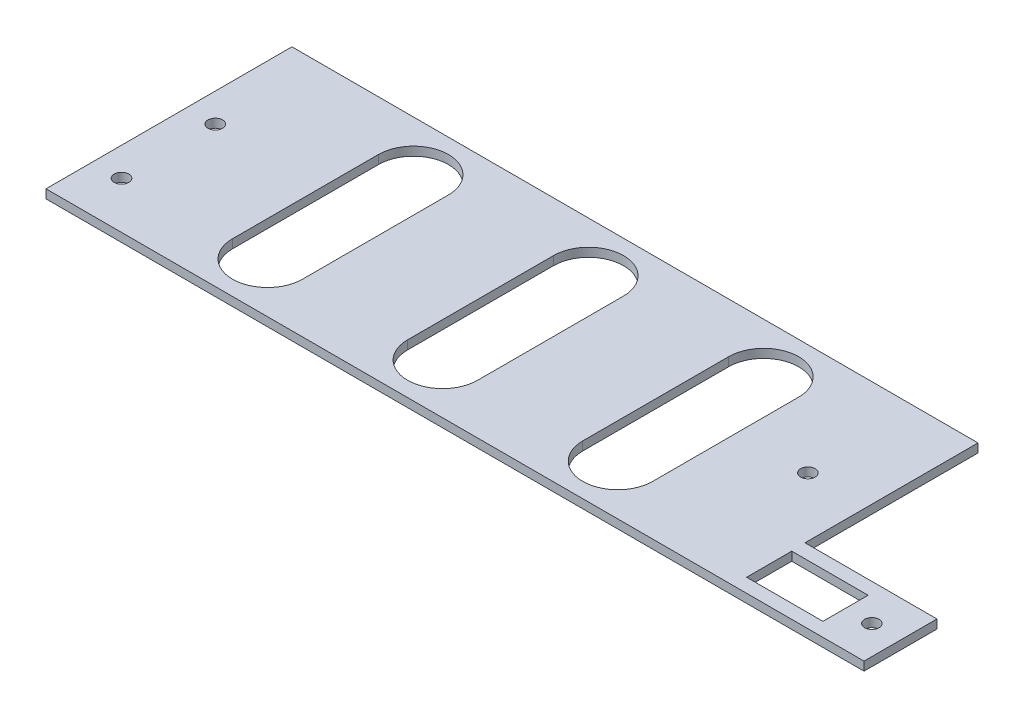
SolidWorks part; units mm, degrees
material "Custom Plastic"
ref_plane "Plan de face" through (0, 0, 0) normal (0, 0, 1) x (1, 0, 0)
ref_plane "Plan de dessus" through (0, 0, 0) normal (0, 1, 0) x (1, 0, 0)
ref_plane "Plan de droite" through (0, 0, 0) normal (1, 0, 0) x (0, 0, -1)
sketch "Esquisse1" plane through (0, 0, 0) normal (0, 1, 0) x (1, 0, 0)
  line L1 (-170.0285, 28.77) -> (110.2715, 28.77) construction
  line L2 (-170.0285, 28.77) -> (-170.0285, -35.5) construction
  line L3 (-170.0285, -35.5) -> (110.2715, -35.5) construction
  line L4 (110.2715, 28.77) -> (110.2715, -35.5) construction
  line L5 (-170.0285, 28.77) -> (110.2715, -35.5) construction
  line L6 (-170.0285, -35.5) -> (110.2715, 28.77) construction
  line L7 (110.2715, 18.77) -> (110.2715, -23) construction
  line L9 (-170.0285, 18.77) -> (-170.0285, -23)
  line L10 (-170.0285, 18.77) -> (-160.0285, 18.77) construction
  line L12 (-170.0285, -35.5) -> (110.2715, -35.5)
  line L13 (110.4715, -10.5) -> (110.4715, -35.5) construction
  line L14 (-160.0285, 28.77) -> (-160.0285, 18.77) construction
  line L15 (65.0578, -2.5147) -> (65.0578, -50002.5147) construction
  line L16 (-170.0285, -23) -> (-160.0285, -23) construction
  line L17 (58.3078, 10.7475) -> (58.3078, -4.4385) construction
  line L18 (-170.2285, -35.5) -> (119.7715, -35.5) construction
  line L19 (-170.0285, 18.77) -> (110.2715, 18.77) construction
  line L21 (110.2715, -23) -> (-170.0285, -23) construction
  line L26 (100.4715, -46.7393) -> (100.4715, -50046.7393) construction
  line L28 (65.0578, 28.77) -> (65.0578, -10.5)
  line L30 (-170.0285, -23) -> (-170.0285, -35.5)
  line L33 (-170.0285, 28.77) -> (-170.0285, 18.77)
  line L34 (-170.0285, 28.77) -> (65.0578, 28.77)
  line L36 (65.0578, -10.5) -> (110.2715, -10.5)
  line L37 (110.2715, -10.5) -> (110.2715, -35.5)
  line L39 (-170.2285, -35.5) -> (-170.2285, -38.5) construction
  line L40 (-170.0285, -35.5) -> (-170.2285, -35.5) construction
  line L41 (110.2715, -35.5) -> (110.4715, -35.5) construction
  line L47 (65.0578, -10.5) -> (119.7715, -10.5) construction
  line L52 (65.0578, 28.77) -> (68.0578, 28.77) construction
  circle A12 centre (100.4715, -23) radius 2.5
  circle A17 centre (-160.2285, -19.4325) radius 2.5
  circle A18 centre (-160.2285, 12.7025) radius 2.5
  circle A20 centre (-160.2285, 12.7025) radius 2.5 construction
  circle A22 centre (-160.2285, -19.4325) radius 2.5 construction
  circle A23 centre (100.4715, -23) radius 2.5 construction
  circle A24 centre (44.8078, 10.7475) radius 2.5
  point P4 (-29.8785, -3.365)
  dimension "D3" = 10
  dimension "D4" = 5
  dimension "D5" = 13.5
  dimension "D7" = 5
  dimension "D1" = 3
  dimension "D2" = 0.2
  dimension "D8" = 0.2
extrude "Boss.-Extru.1" add sketch "Esquisse1" along normal blind 3
sketch "Esquisse2" plane through (0, 3, 0) normal (0, 1, 0) x (1, 0, 0)
  line L0 (-170.0285, 28.77) -> (-170.0285, 38.77) construction
  line L1 (-170.0285, 38.77) -> (-52.4853, 38.77) construction
  line L2 (65.0578, 38.77) -> (65.0578, 28.77) construction
  line L3 (65.0578, -3.365) -> (80.0824, -3.365) construction
  line L4 (100.4715, -23) -> (117.6885, -23) construction
  line L5 (-170.0285, 28.77) -> (-170.0285, -35.5) construction
  line L6 (-52.4853, 38.77) -> (65.0578, 38.77) construction
  line L7 (-111.2569, 38.77) -> (-111.2569, 50038.77) construction
  line L8 (-52.4853, 38.77) -> (-52.4853, 50038.77) construction
  line L9 (6.2862, 38.77) -> (6.2862, 50038.77) construction
  line L10 (-113.7569, 11.635) -> (-113.7569, -18.365)
  line L11 (-108.7569, -18.365) -> (-108.7569, 11.635)
  line L12 (-113.7569, 11.635) -> (-108.7569, 11.635) construction
  line L13 (-108.7569, -18.365) -> (-113.7569, -18.365) construction
  line L14 (-113.7569, -3.365) -> (-108.7569, -3.365) construction
  line L15 (-54.9853, 11.635) -> (-54.9853, -18.365)
  line L16 (-49.9853, -18.365) -> (-49.9853, 11.635)
  line L17 (-54.9853, 11.635) -> (-49.9853, 11.635) construction
  line L18 (-49.9853, -18.365) -> (-54.9853, -18.365) construction
  line L19 (-54.9853, -3.365) -> (-49.9853, -3.365) construction
  line L20 (3.7862, 11.635) -> (3.7862, -18.365)
  line L21 (8.7862, -18.365) -> (8.7862, 11.635)
  line L22 (3.7862, 11.635) -> (8.7862, 11.635) construction
  line L23 (8.7862, -18.365) -> (3.7862, -18.365) construction
  line L24 (3.7862, -3.365) -> (8.7862, -3.365) construction
  line L25 (85.2715, -23) -> (85.2715, -50023) construction
  line L26 (110.2715, -35.5) -> (110.2715, -10.5) construction
  line L27 (85.2715, -18) -> (65.2715, -18)
  line L28 (65.2715, -18) -> (65.2715, -28)
  line L29 (65.2715, -28) -> (85.2715, -28)
  line L30 (85.2715, -28) -> (85.2715, -18)
  arc A0 (-108.7569, 11.635) -> (-113.7569, 11.635) centre (-111.2569, 11.635) ccw
  arc A1 (-108.7569, -18.365) -> (-113.7569, -18.365) centre (-111.2569, -18.365) cw
  arc A2 (-49.9853, 11.635) -> (-54.9853, 11.635) centre (-52.4853, 11.635) ccw
  arc A3 (-49.9853, -18.365) -> (-54.9853, -18.365) centre (-52.4853, -18.365) cw
  arc A4 (8.7862, 11.635) -> (3.7862, 11.635) centre (6.2862, 11.635) ccw
  arc A5 (8.7862, -18.365) -> (3.7862, -18.365) centre (6.2862, -18.365) cw
  point P7 (-170.0285, -3.365)
  point P8 (-111.2569, 38.77)
  point P13 (6.2862, 38.77)
  point P26 (-111.2569, -3.365)
  point P30 (100.4715, -23)
  point P37 (-52.4853, -3.365)
  point P46 (6.2862, -3.365)
  point P58 (65.2715, -23)
  dimension "D1" = 10
  dimension "D2" = 5
  dimension "D3" = 30
  dimension "D4" = 25
  dimension "D5" = 10
  dimension "D6" = 20
extrude "Enlèv. mat.-Extru.1" cut sketch "Esquisse2" against normal through all
sketch "Sketch1" plane through (0, 0, -28.77) normal (0, 0, -1) x (-1, 0, 0)
  line L1 (170.0285, 0) -> (-65.0578, 0)
  line L2 (170.0285, 0) -> (170.0285, 3)
  line L3 (170.0285, 3) -> (-65.0578, 3)
  line L4 (-65.0578, 0) -> (-65.0578, 3)
extrude "Boss-Extrude1" add sketch "Sketch1" along normal blind 20
sketch "Sketch2" plane through (0, 0, 0) normal (0, -1, 0) x (-1, 0, 0)
  line L0 (111.2569, -18.365) -> (111.2569, 31.635) construction
  line L1 (111.2569, -18.365) -> (111.2569, 31.635) construction
  line L2 (99.2569, -18.365) -> (99.2569, 31.635)
  line L3 (123.2569, -18.365) -> (123.2569, 31.635)
  line L4 (51.2569, -18.365) -> (51.2569, 31.635) construction
  line L5 (39.2569, -18.365) -> (39.2569, 31.635)
  line L6 (63.2569, -18.365) -> (63.2569, 31.635)
  line L7 (-8.7431, -18.365) -> (-8.7431, 31.635) construction
  line L8 (-20.7431, -18.365) -> (-20.7431, 31.635)
  line L9 (3.2569, -18.365) -> (3.2569, 31.635)
  arc A1 (99.2569, -18.365) -> (123.2569, -18.365) centre (111.2569, -18.365) ccw
  arc A2 (123.2569, 31.635) -> (99.2569, 31.635) centre (111.2569, 31.635) ccw
  arc A3 (39.2569, -18.365) -> (63.2569, -18.365) centre (51.2569, -18.365) ccw
  arc A4 (63.2569, 31.635) -> (39.2569, 31.635) centre (51.2569, 31.635) ccw
  arc A5 (-20.7431, -18.365) -> (3.2569, -18.365) centre (-8.7431, -18.365) ccw
  arc A6 (3.2569, 31.635) -> (-20.7431, 31.635) centre (-8.7431, 31.635) ccw
  point P2 (111.2569, 6.635)
  point P12 (51.2569, 6.635)
  point P19 (-8.7431, 6.635)
  dimension "D2" = 12
  dimension "D1" = 50
  dimension "D3" = 3
extrude "Cut-Extrude1" cut sketch "Sketch2" against normal blind 10
sketch "Sketch3" plane through (0, 3, 0) normal (0, 1, 0) x (1, 0, 0)
  line L1 (85.2715, -30.7406) -> (65.2715, -30.7406)
  line L2 (85.2715, -30.7406) -> (85.2715, -15.2594)
  line L3 (85.2715, -15.2594) -> (65.2715, -15.2594)
  line L4 (65.2715, -30.7406) -> (65.2715, -15.2594)
  line L5 (85.2715, -30.7406) -> (65.2715, -15.2594) construction
  line L6 (85.2715, -15.2594) -> (65.2715, -30.7406) construction
  line L7 (85.2715, -15.2594) -> (91.4365, -15.2594)
  line L8 (85.2715, -15.2594) -> (85.2715, -30.7406)
  line L9 (85.2715, -30.7406) -> (91.4365, -30.7406)
  line L10 (91.4365, -15.2594) -> (91.4365, -30.7406)
  point P0 (75.2715, -23)
  line M13 (65.2715, -18) -> (85.2715, -18)
  line M14 (85.2715, -18) -> (85.2715, -28)
  line M15 (85.2715, -28) -> (65.2715, -28)
extrude "Cut-Extrude2" cut sketch "Sketch3" against normal blind 10 contours L10 L7 L2 L9 M14 | L4 L2 L3 M13 | L4 L1 L2 M15
